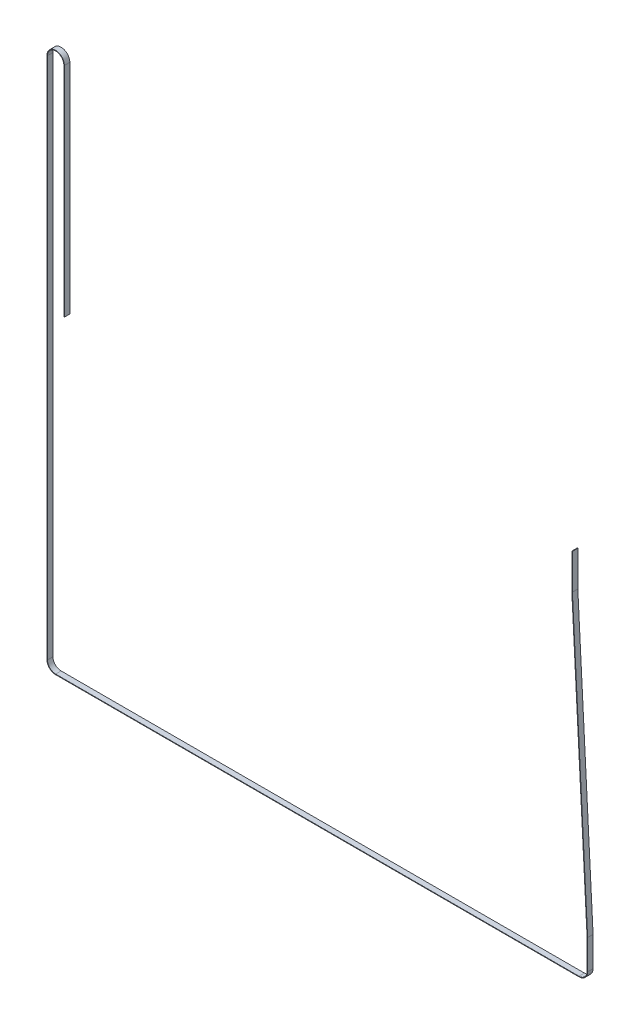
SolidWorks part; units mm, degrees
ref_plane "Ebene vorne" through (0, 0, 0) normal (0, 0, 1) x (1, 0, 0)
ref_plane "Ebene oben" through (0, 0, 0) normal (0, 1, 0) x (1, 0, 0)
ref_plane "Ebene rechts" through (0, 0, 0) normal (1, 0, 0) x (0, 0, -1)
sketch "Skizze1" plane through (0, 0, 0) normal (0, 0, 1) x (1, 0, 0)
  line L0 (-240, 0) -> (240, 0) construction
  line L1 (-240, 0) -> (-240, 480) construction
  line L2 (240, 0) -> (240, 300) construction
  line L3 (-232.5, 480) -> (-232.5, 280)
  line L4 (240, -7.5) -> (-240, -7.5)
  line L5 (-247.5, 0) -> (-247.5, 480)
  line L6 (247.5, 0) -> (247.5, 27.187)
  line L7 (247.5, 27.187) -> (233.5, 294.5771)
  line L8 (233.5, 294.5771) -> (233.5, 326.9614)
  circle A0 centre (-240, 480) radius 7.5 construction
  circle A1 centre (-240, 0) radius 7.5 construction
  circle A2 centre (240, 0) radius 7.5 construction
  circle A3 centre (-222.5, 280) radius 10 construction
  arc A4 (-232.5, 480) -> (-247.5, 480) centre (-240, 480) ccw
  arc A5 (-247.5, 0) -> (-240, -7.5) centre (-240, 0) ccw
  arc A6 (247.5, 0) -> (240, -7.5) centre (240, 0) cw
  arc A7 (-232.5, 280) -> (-214.4376, 274.0841) centre (-222.5, 280) ccw construction
  dimension "D4" = 15
  dimension "D5" = 20
  dimension "D1" = 480
  dimension "D2" = 480
  dimension "D3" = 300
  dimension "D6" = 200
  dimension "D7" = 17.5
  dimension "D8" = 14
extrude "Linear-Austragen-Dünn1" add sketch "Skizze1" along normal mid plane 5 thin thin type one direction reverse wall 0.5
